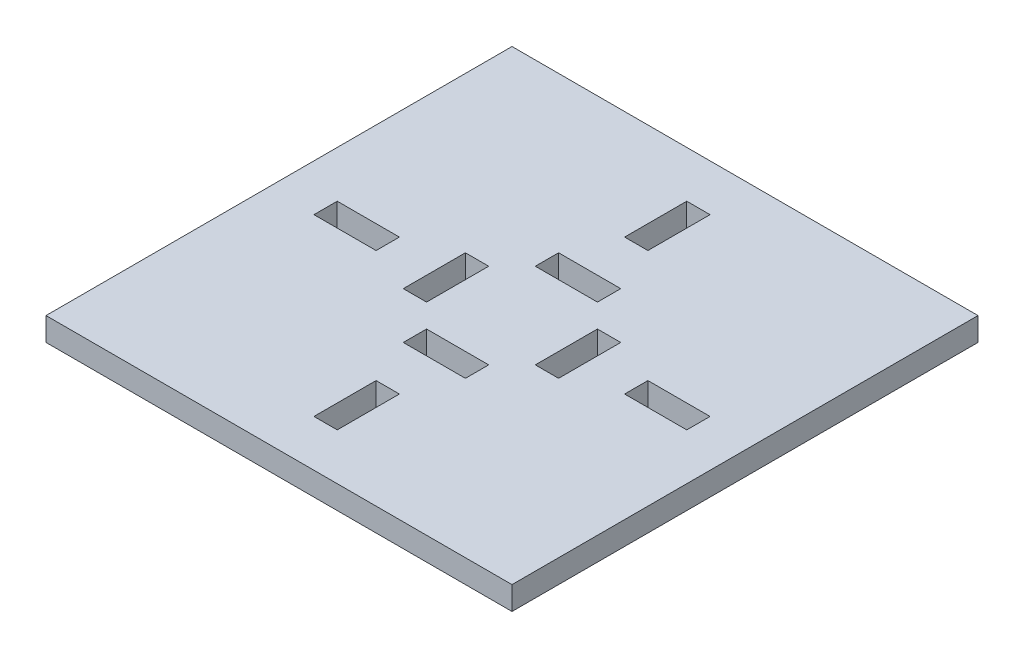
SolidWorks part; units mm, degrees
ref_plane "Alzado" through (0, 0, 0) normal (0, 0, 1) x (1, 0, 0)
ref_plane "Planta" through (0, 0, 0) normal (0, 1, 0) x (1, 0, 0)
ref_plane "Vista lateral" through (0, 0, 0) normal (1, 0, 0) x (0, 0, -1)
sketch "Croquis1" plane through (0, 0, 0) normal (0, 1, 0) x (1, 0, 0)
  line L0 (0, 0) -> (0, 10) construction
  line L1 (-30, 30) -> (30, 30)
  line L2 (-30, 30) -> (-30, -30)
  line L3 (-30, -30) -> (30, -30)
  line L4 (30, 30) -> (30, -30)
  line L5 (-30, 30) -> (30, -30) construction
  line L6 (-30, -30) -> (30, 30) construction
  line L7 (0, 10) -> (-4, 10)
  line L8 (-4, 10) -> (-4, 7)
  line L9 (-4, 7) -> (4, 7)
  line L10 (4, 7) -> (4, 10)
  line L11 (4, 10) -> (0, 10)
  line L12 (7, 4) -> (7, -4)
  line L13 (7, -4) -> (10, -4)
  line L14 (10, -4) -> (10, 0)
  line L15 (10, 0) -> (10, 4)
  line L16 (10, 4) -> (7, 4)
  line L17 (4, -7) -> (-4, -7)
  line L18 (-4, -7) -> (-4, -10)
  line L19 (-4, -10) -> (0, -10)
  line L20 (0, -10) -> (4, -10)
  line L21 (4, -10) -> (4, -7)
  line L22 (-7, -4) -> (-7, 4)
  line L23 (-7, 4) -> (-10, 4)
  line L24 (-10, 4) -> (-10, 0)
  line L25 (-10, 0) -> (-10, -4)
  line L26 (-10, -4) -> (-7, -4)
  line L27 (10, 0) -> (30, 0) construction
  line L28 (20, 0) -> (20, 1.5) construction
  line L29 (20, 1.5) -> (16, 1.5)
  line L30 (16, 1.5) -> (16, -1.5)
  line L31 (16, -1.5) -> (24, -1.5)
  line L32 (24, -1.5) -> (24, 1.5)
  line L33 (24, 1.5) -> (20, 1.5)
  line L34 (1.5, -20) -> (1.5, -16)
  line L35 (1.5, -24) -> (1.5, -20)
  line L36 (1.5, -16) -> (-1.5, -16)
  line L37 (-1.5, -16) -> (-1.5, -24)
  line L38 (-1.5, -24) -> (1.5, -24)
  line L39 (-20, -1.5) -> (-16, -1.5)
  line L40 (-24, -1.5) -> (-20, -1.5)
  line L41 (-16, -1.5) -> (-16, 1.5)
  line L42 (-16, 1.5) -> (-24, 1.5)
  line L43 (-24, 1.5) -> (-24, -1.5)
  line L44 (-1.5, 20) -> (-1.5, 16)
  line L45 (-1.5, 24) -> (-1.5, 20)
  line L46 (-1.5, 16) -> (1.5, 16)
  line L47 (1.5, 16) -> (1.5, 24)
  line L48 (1.5, 24) -> (-1.5, 24)
  point P0 (0, 0)
  point P30 (0, 0)
  point P53 (0, 0)
  dimension "D1" = 60
  dimension "D2" = 60
  dimension "D3" = 10
  dimension "D4" = 4
  dimension "D5" = 3
  dimension "D6" = 8
  dimension "D8" = 20
  dimension "D9" = 1.5
  dimension "D10" = 4
  dimension "D11" = 3
  dimension "D12" = 8
  dimension "D7" = 4
  dimension "D13" = 4
extrude "Saliente-Extruir1" add sketch "Croquis1" along normal blind 3
